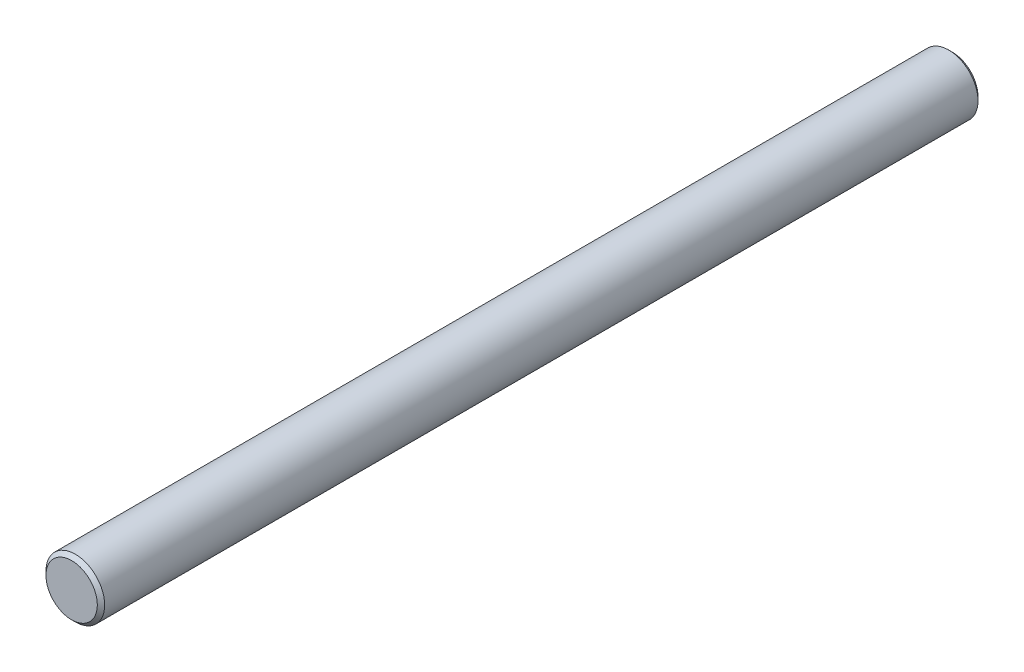
SolidWorks part; units mm, degrees
ref_plane "Front Plane" through (0, 0, 0) normal (0, 0, 1) x (1, 0, 0)
ref_plane "Top Plane" through (0, 0, 0) normal (0, 1, 0) x (1, 0, 0)
ref_plane "Right Plane" through (0, 0, 0) normal (1, 0, 0) x (0, 0, -1)
sketch "Sketch1" plane through (0, 0, 0) normal (0, 0, 1) x (1, 0, 0)
  circle A0 centre (0, 0) radius 4
extrude "Boss-Extrude1" add sketch "Sketch1" along normal blind 120
chamfer "Chamfer1" distance 0.5 angle 45 2 edges at (4, 0, 120) (4, 0, 0)
